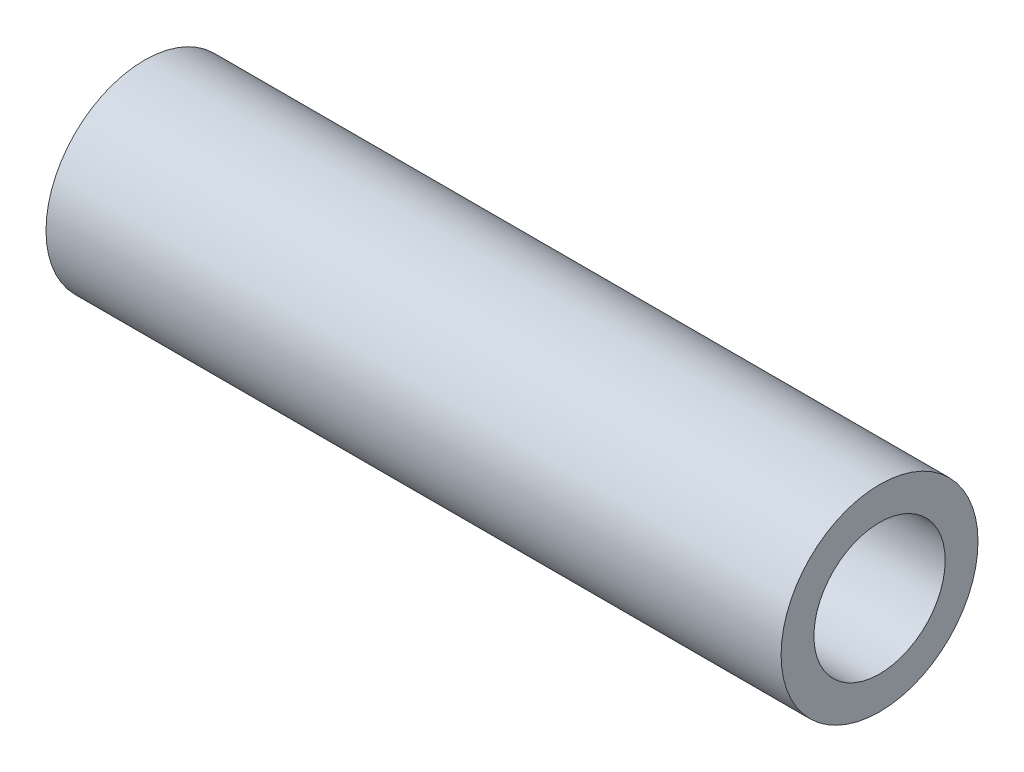
SolidWorks part; units mm, degrees
material "Delrin 2700 NC010, Low Viscosity Acetal Copolymer (SS)"
ref_plane "Front Plane" through (0, 0, 0) normal (0, 0, 1) x (1, 0, 0)
ref_plane "Top Plane" through (0, 0, 0) normal (0, 1, 0) x (1, 0, 0)
ref_plane "Right Plane" through (0, 0, 0) normal (1, 0, 0) x (0, 0, -1)
sketch "Sketch1" plane through (0, 0, 0) normal (1, 0, 0) x (0, 0, -1)
  circle A0 centre (0, 0) radius 2.3813
  circle A1 centre (0, 0) radius 1.5875
  dimension "D1" = 4.7625
  dimension "D2" = 3.175
extrude "Boss-Extrude1" add sketch "Sketch1" along normal blind 17.78
